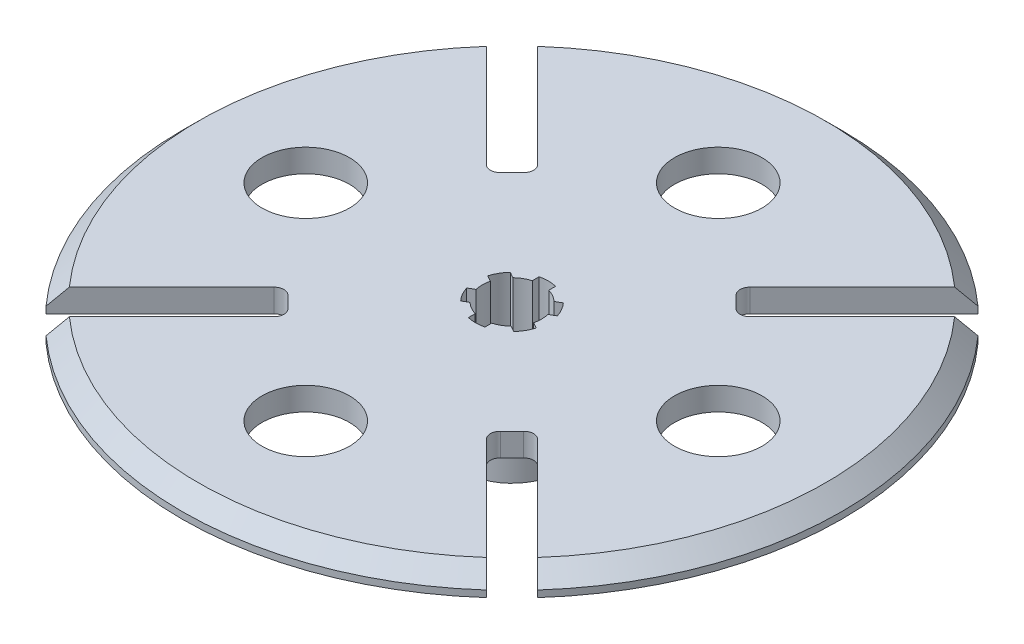
SolidWorks part; units mm, degrees
ref_plane "前视基准面" through (0, 0, 0) normal (0, 0, 1) x (1, 0, 0)
ref_plane "上视基准面" through (0, 0, 0) normal (0, 1, 0) x (1, 0, 0)
ref_plane "右视基准面" through (0, 0, 0) normal (1, 0, 0) x (0, 0, -1)
sketch "草图1" plane through (0, 0, 0) normal (0, 1, 0) x (1, 0, 0)
  circle A0 centre (0, 0) radius 9
  circle A1 centre (0, 0) radius 15
  dimension "D1" = 18
  dimension "D2" = 30
extrude "凸台-拉伸1" add sketch "草图1" along normal blind 30
sketch "草图2" plane through (0, 30, 0) normal (0, 1, 0) x (1, 0, 0)
  circle A0 centre (0, 0) radius 100
  circle M1 centre (0, 0) radius 15
  circle M2 centre (0, 0) radius 9
  dimension "D1" = 200
extrude "凸台-拉伸2" add sketch "草图2" along normal blind 7 contours M1 M2 | A0 M1
sketch "草图7" plane through (0, 37, 0) normal (0, 1, 0) x (1, 0, 0)
  line L1 (-2.5, -10.7121) -> (2.5, -10.7121) construction
  line L2 (-2.5, -10.7121) -> (-2.5, 10.7121)
  line L3 (-2.5, 10.7121) -> (2.5, 10.7121) construction
  line L4 (2.5, -10.7121) -> (2.5, 10.7121)
  line L5 (-2.5, -10.7121) -> (2.5, 10.7121) construction
  line L6 (-2.5, 10.7121) -> (2.5, -10.7121) construction
  arc A0 (-2.5, -10.7121) -> (2.5, -10.7121) centre (0, 0) ccw
  arc A1 (-2.5, 10.7121) -> (-2.5, -10.7121) centre (0, 0) ccw construction
  arc A2 (2.5, -10.7121) -> (2.5, 10.7121) centre (0, 0) ccw construction
  arc A3 (2.5, 10.7121) -> (-2.5, 10.7121) centre (0, 0) ccw
  dimension "D1" = 22
  dimension "D2" = 5
extrude "切除-拉伸1" cut sketch "草图7" against normal through all
pattern_circular "阵列(圆周)1" count 6 over 360 about axis through (0, 0, 0) along (0, 1, 0) of "切除-拉伸1"
fillet "圆角1" radius 10 1 edges at (0, 30, 15)
sketch "草图8" plane through (0, 37, 0) normal (0, 1, 0) x (1, 0, 0)
  circle A0 centre (0, 0) radius 62.5 construction
  point P3 (62.5, 0)
  point P7 (0, -62.5)
  point P8 (-62.5, 0)
  point P9 (0, 62.5)
  dimension "D1" = 125
  dimension "D2" = 4
hole_wizard "M30 螺纹孔1" positions "草图8" profile "草图9" tap size "M30" standard "GB"
sketch "草图9" plane through (0, 37, -62.5) normal (1, 0, 0) x (0, 0, 1)
  line L0 (0, 0) -> (0, 70.5)
  line L1 (0, 70.5) -> (13.25, 62.5386)
  line L2 (13.25, 62.5386) -> (13.25, 0)
  line L5 (13.25, 0) -> (0, 0)
  line L10 (0, 70.5) -> (-13.25, 62.5386) construction
  line L11 (0, -6.35) -> (0, 107.95) construction
  dimension "螺纹孔钻头直径" = 26.5
  dimension "螺纹孔钻头深度" = 70.5
  dimension "导头角度" = 118
cosmetic thread "孔螺纹线1" parameters "D1"=60, "D2"=30
cosmetic thread "孔螺纹线2" parameters "D1"=60, "D2"=30
cosmetic thread "孔螺纹线3" parameters "D1"=60, "D2"=30
cosmetic thread "孔螺纹线4" parameters "D1"=60, "D2"=30
chamfer "倒角1" distance 5 angle 45 1 edges at (0, 37, 100)
sketch "草图10" plane through (0, 30, 0) normal (0, -1, 0) x (1, 0, 0)
  line L0 (0, 0) -> (70.7107, -70.7107) construction
  line L1 (20.35, 0) -> (-20.35, 0) construction
  line L2 (33.9411, -33.9411) -> (70.7107, -70.7107)
  circle A0 centre (0, 0) radius 100 construction
  point P7 (33.9411, -33.9411)
  dimension "D1" = 45
  dimension "D2" = 48
extrude "切除-拉伸-薄壁1" cut sketch "草图10" against normal through all and the other way through all thin thin type mid plane wall 11
pattern_circular "阵列(圆周)2" count 4 over 360 about axis through (0, 0, 0) along (0, 1, 0) of "切除-拉伸-薄壁1"
fillet "圆角2" radius 3 8 edges at (30.052, 33.5, -37.8302) (37.8302, 33.5, -30.052) (37.8302, 33.5, 30.052) (30.052, 33.5, 37.8302) (-30.052, 33.5, 37.8302) (-37.8302, 33.5, 30.052) (-37.8302, 33.5, -30.052) (-30.052, 33.5, -37.8302)
